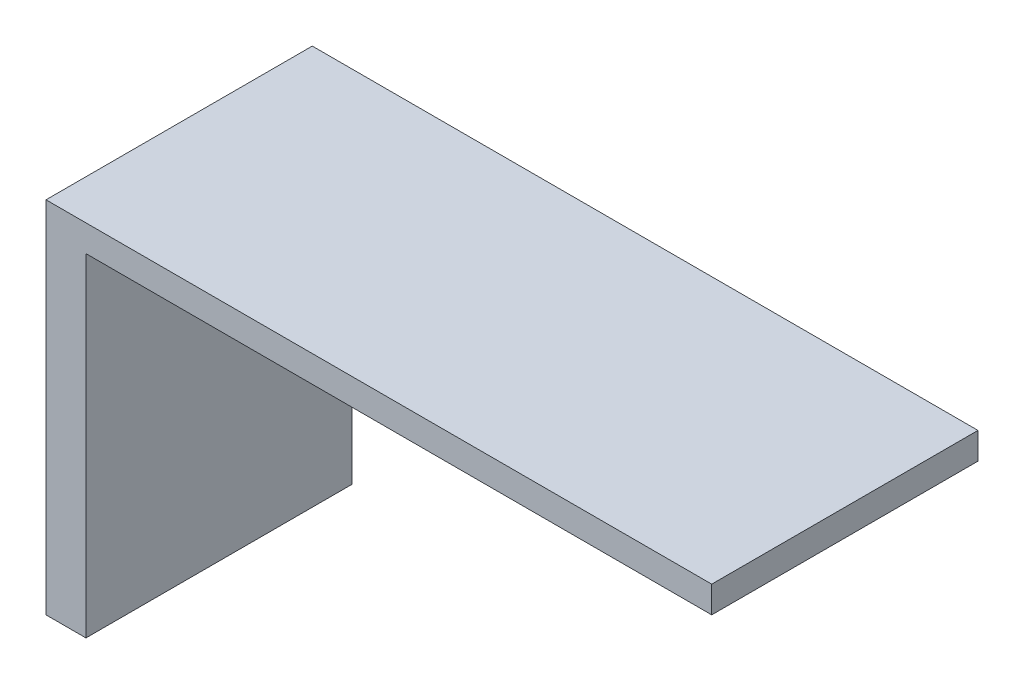
SolidWorks part; units mm, degrees
ref_plane "Front Plane" through (0, 0, 0) normal (0, 0, 1) x (1, 0, 0)
ref_plane "Top Plane" through (0, 0, 0) normal (0, 1, 0) x (1, 0, 0)
ref_plane "Right Plane" through (0, 0, 0) normal (1, 0, 0) x (0, 0, -1)
sketch "Sketch1" plane through (0, 0, 0) normal (0, 1, 0) x (1, 0, 0)
  line L1 (0, 0) -> (50, 0)
  line L2 (0, 0) -> (0, 20)
  line L3 (0, 20) -> (50, 20)
  line L4 (50, 0) -> (50, 20)
  dimension "D1" = 50
  dimension "D2" = 20
extrude "Boss-Extrude1" add sketch "Sketch1" along normal blind 2
sketch "Sketch2" plane through (0, 0, 0) normal (0, -1, 0) x (1, 0, 0)
  line L0 (50, -20) -> (0, -20) construction
  line L1 (0, 0) -> (3, 0)
  line L2 (0, 0) -> (0, -20)
  line L3 (0, -20) -> (3, -20)
  line L4 (3, 0) -> (3, -20)
  dimension "D1" = 3
extrude "Boss-Extrude2" add sketch "Sketch2" along normal blind 25
